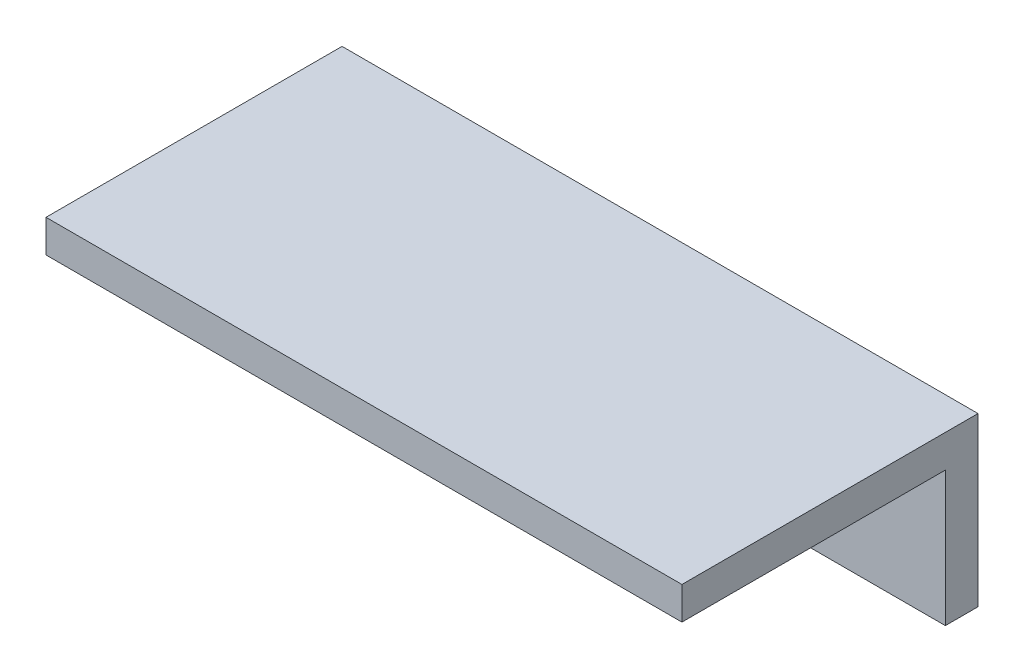
SolidWorks part; units mm, degrees
ref_plane "前基準面" through (0, 0, 0) normal (0, 0, 1) x (1, 0, 0)
ref_plane "上基準面" through (0, 0, 0) normal (0, 1, 0) x (1, 0, 0)
ref_plane "右基準面" through (0, 0, 0) normal (1, 0, 0) x (0, 0, -1)
sketch "草圖1" plane through (0, 0, 0) normal (0, 0, 1) x (1, 0, 0)
  line L1 (34.1, -8.975) -> (-34.1, -8.975)
  line L2 (34.1, -8.975) -> (34.1, 8.975)
  line L3 (34.1, 8.975) -> (-34.1, 8.975)
  line L4 (-34.1, -8.975) -> (-34.1, 8.975)
  line L5 (0, 8.975) -> (0, -8.975) construction
  line L6 (34.1, 0) -> (-34.1, 0) construction
  point P0 (0, 0)
  point P4 (0, -8.975)
  point P5 (0, 8.975)
  point P6 (0, 0)
  dimension "D1" = 17.95
  dimension "D2" = 68.2
extrude "1" add sketch "草圖1" along normal blind 3.5
sketch "草圖21" plane through (0, 0, 3.5) normal (0, 0, 1) x (1, 0, 0)
  line L0 (34.1, -8.975) -> (34.1, 8.975) construction
  line L1 (-34.1, 8.975) -> (34.1, 8.975)
  line L2 (-34.1, 8.975) -> (-34.1, 5.475)
  line L3 (-34.1, 5.475) -> (34.1, 5.475)
  line L4 (34.1, 8.975) -> (34.1, 5.475)
  dimension "D1" = 3.5
extrude "填料-伸長4" add sketch "草圖21" along normal blind 28.25
sketch "草圖24" plane through (0, 0, 0) normal (0, 0, -1) x (-1, 0, 0)
  line L0 (0, -8.975) -> (0, -5.975) construction
  line L1 (34.1, -8.975) -> (-34.1, -8.975) construction
  circle A0 centre (0, -3.0705) radius 2.85
  dimension "D1" = 5.7
extrude "除料-伸長2" cut sketch "草圖24" against normal blind 28.25
